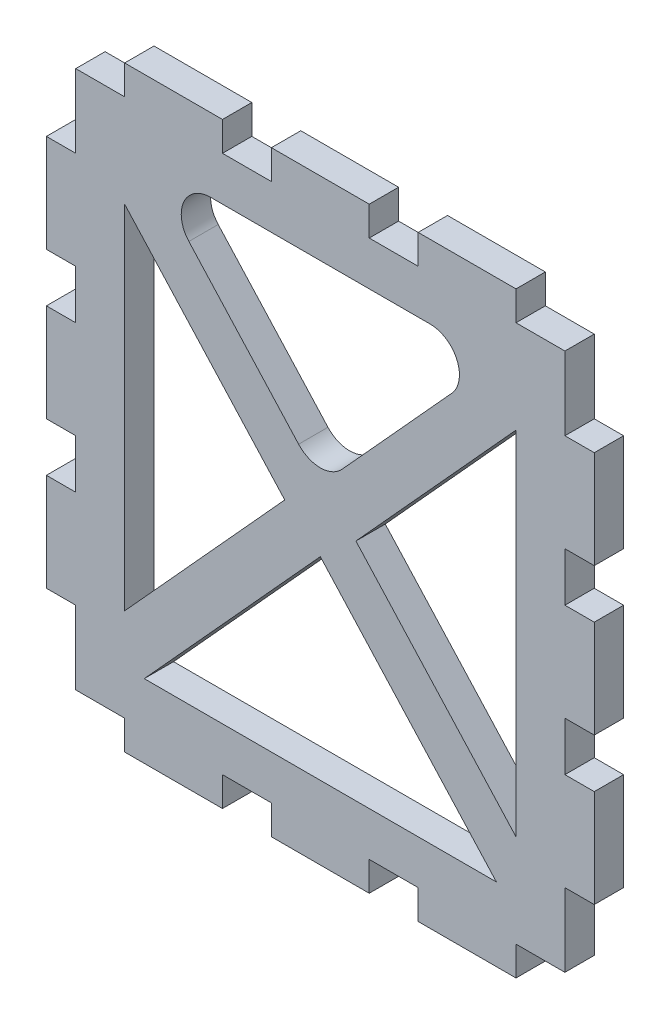
SolidWorks part; units mm, degrees
material "轻木"
ref_plane "前视基准面" through (0, 0, 0) normal (0, 0, 1) x (1, 0, 0)
ref_plane "上视基准面" through (0, 0, 0) normal (0, 1, 0) x (1, 0, 0)
ref_plane "右视基准面" through (0, 0, 0) normal (1, 0, 0) x (0, 0, -1)
sketch "草图1" plane through (0, 0, 0) normal (0, 0, 1) x (1, 0, 0)
  line L1 (-25, 27.5) -> (-20, 27.5)
  line L2 (-25, 27.5) -> (-25, 20)
  line L3 (-25, -27.5) -> (-20, -27.5)
  line L4 (25, 27.5) -> (25, 20)
  line L7 (-25, 20) -> (-28, 20)
  line L9 (-25, 10) -> (-28, 10)
  line L10 (-28, 20) -> (-28, 10)
  line L11 (-25, 5) -> (-28, 5)
  line L12 (-28, 5) -> (-28, -5)
  line L13 (-25, -5) -> (-28, -5)
  line L15 (-25, -10) -> (-28, -10)
  line L16 (-28, -10) -> (-28, -20)
  line L17 (-25, -20) -> (-28, -20)
  line L18 (0, -55) -> (0, 55) construction
  line L19 (25, -10) -> (28, -10)
  line L20 (28, -10) -> (28, -20)
  line L21 (25, -20) -> (28, -20)
  line L23 (25, 5) -> (28, 5)
  line L24 (28, 5) -> (28, -5)
  line L25 (25, -5) -> (28, -5)
  line L27 (25, 10) -> (28, 10)
  line L28 (28, 20) -> (28, 10)
  line L29 (25, 20) -> (28, 20)
  line L31 (-5, 27.5) -> (-5, 30.5)
  line L33 (-20, 27.5) -> (-20, 30.5)
  line L34 (-20, 30.5) -> (-10, 30.5)
  line L35 (-10, 27.5) -> (-10, 30.5)
  line L37 (5, 27.5) -> (5, 30.5)
  line L38 (-5, 30.5) -> (5, 30.5)
  line L39 (10, 27.5) -> (10, 30.5)
  line L41 (20, 27.5) -> (20, 30.5)
  line L42 (10, 30.5) -> (20, 30.5)
  line L43 (55, 0) -> (-55, 0) construction
  line L45 (20, -27.5) -> (20, -30.5)
  line L46 (10, -30.5) -> (20, -30.5)
  line L47 (10, -27.5) -> (10, -30.5)
  line L49 (5, -27.5) -> (5, -30.5)
  line L50 (-5, -30.5) -> (5, -30.5)
  line L51 (-5, -27.5) -> (-5, -30.5)
  line L52 (-20, -30.5) -> (-10, -30.5)
  line L53 (-10, -27.5) -> (-10, -30.5)
  line L55 (-20, -27.5) -> (-20, -30.5)
  line L56 (-25, 10) -> (-25, 5)
  line L57 (-25, -5) -> (-25, -10)
  line L58 (-25, -20) -> (-25, -27.5)
  line L59 (-10, -27.5) -> (-5, -27.5)
  line L60 (5, -27.5) -> (10, -27.5)
  line L61 (20, -27.5) -> (25, -27.5)
  line L62 (25, -20) -> (25, -27.5)
  line L63 (25, -5) -> (25, -10)
  line L64 (25, 10) -> (25, 5)
  line L65 (20, 27.5) -> (25, 27.5)
  line L67 (5, 27.5) -> (10, 27.5)
  line L69 (-10, 27.5) -> (-5, 27.5)
  point P0 (0, 0)
  dimension "D1" = 50
  dimension "D2" = 55
  dimension "D3" = 3
  dimension "D4" = 10
  dimension "D5" = 7.5
  dimension "D7" = 3
  dimension "D8" = 10
  dimension "D9" = 5
  dimension "D6" = 3
  dimension "D10" = 3
extrude "凸台-拉伸1" add sketch "草图1" along normal blind 3
sketch "草图2" plane through (0, 0, 3) normal (0, 0, 1) x (1, 0, 0)
  line L0 (-25, 27.5) -> (25, -27.5) construction
  line L1 (25, 27.5) -> (-25, -27.5) construction
  line L3 (0, -1.65) -> (0, 1.65) construction
  line L4 (-18, 23) -> (18, 23)
  line L5 (18, 23) -> (0, 3.2)
  line L6 (-18, 23) -> (0, 3.2)
  line L7 (1.65, 0) -> (-1.65, 0) construction
  line L8 (-18, -23) -> (18, -23)
  line L9 (18, -23) -> (0, -3.2)
  line L10 (-18, -23) -> (0, -3.2)
  line L12 (20, 18) -> (20, -18)
  line L13 (20, -18) -> (3.6364, 0)
  line L14 (20, 18) -> (3.6364, 0)
  line L15 (-20, 18) -> (-3.6364, 0)
  line L16 (-20, -18) -> (-3.6364, 0)
  line L17 (-20, 18) -> (-20, -18)
extrude "切除-拉伸1" cut sketch "草图2" against normal blind 10
fillet "圆角2" radius 3 3 edges at (18, 23, 1.5) (0, 3.2, 1.5) (-18, 23, 1.5)
